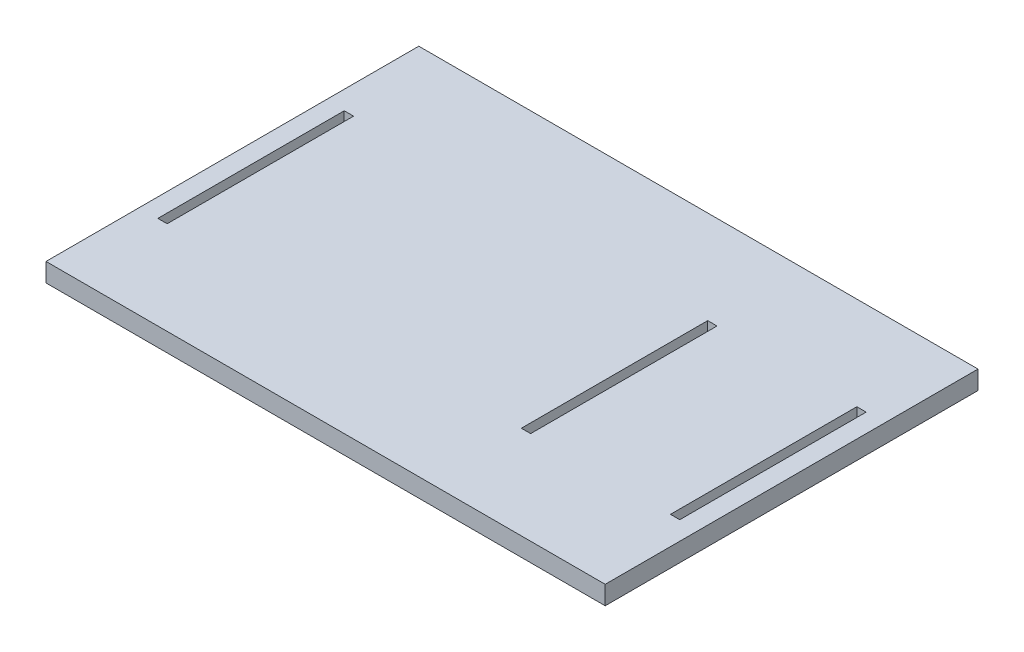
SolidWorks part; units mm, degrees
ref_plane "Alzado" through (0, 0, 0) normal (0, 0, 1) x (1, 0, 0)
ref_plane "Planta" through (0, 0, 0) normal (0, 1, 0) x (1, 0, 0)
ref_plane "Vista lateral" through (0, 0, 0) normal (1, 0, 0) x (0, 0, -1)
sketch "Croquis1" plane through (0, 0, 0) normal (0, 1, 0) x (1, 0, 0)
  line L0 (-150, 0) -> (150, 0) construction
  line L1 (-150, -100) -> (150, -100)
  line L2 (-150, -100) -> (-150, 100)
  line L3 (-150, 100) -> (150, 100)
  line L4 (150, -100) -> (150, 100)
  line L5 (-150, -100) -> (150, 100) construction
  line L6 (-150, 100) -> (150, -100) construction
  line L7 (140, -50) -> (140, 50)
  line L8 (-140, -50) -> (-135, -50)
  line L9 (-140, -50) -> (-140, 50)
  line L10 (-140, 50) -> (-135, 50)
  line L11 (-135, -50) -> (-135, 50)
  line L12 (-140, -50) -> (-135, 50) construction
  line L13 (-140, 50) -> (-135, -50) construction
  line L14 (55, -50) -> (60, -50)
  line L15 (55, -50) -> (55, 50)
  line L16 (55, 50) -> (60, 50)
  line L17 (60, -50) -> (60, 50)
  line L18 (55, -50) -> (60, 50) construction
  line L19 (55, 50) -> (60, -50) construction
  line L20 (135, -50) -> (140, -50)
  line L21 (135, -50) -> (135, 50)
  line L22 (135, 50) -> (140, 50)
  point P0 (0, 0)
  point P8 (-137.5, 0)
  point P13 (57.5, 0)
  dimension "D1" = 200
  dimension "D2" = 300
  dimension "D3" = 100
  dimension "D4" = 10
  dimension "D5" = 5
  dimension "D6" = 5
  dimension "D7" = 90
  dimension "D9" = 10
  dimension "D8" = 2
extrude "Saliente-Extruir1" add sketch "Croquis1" along normal blind 10
